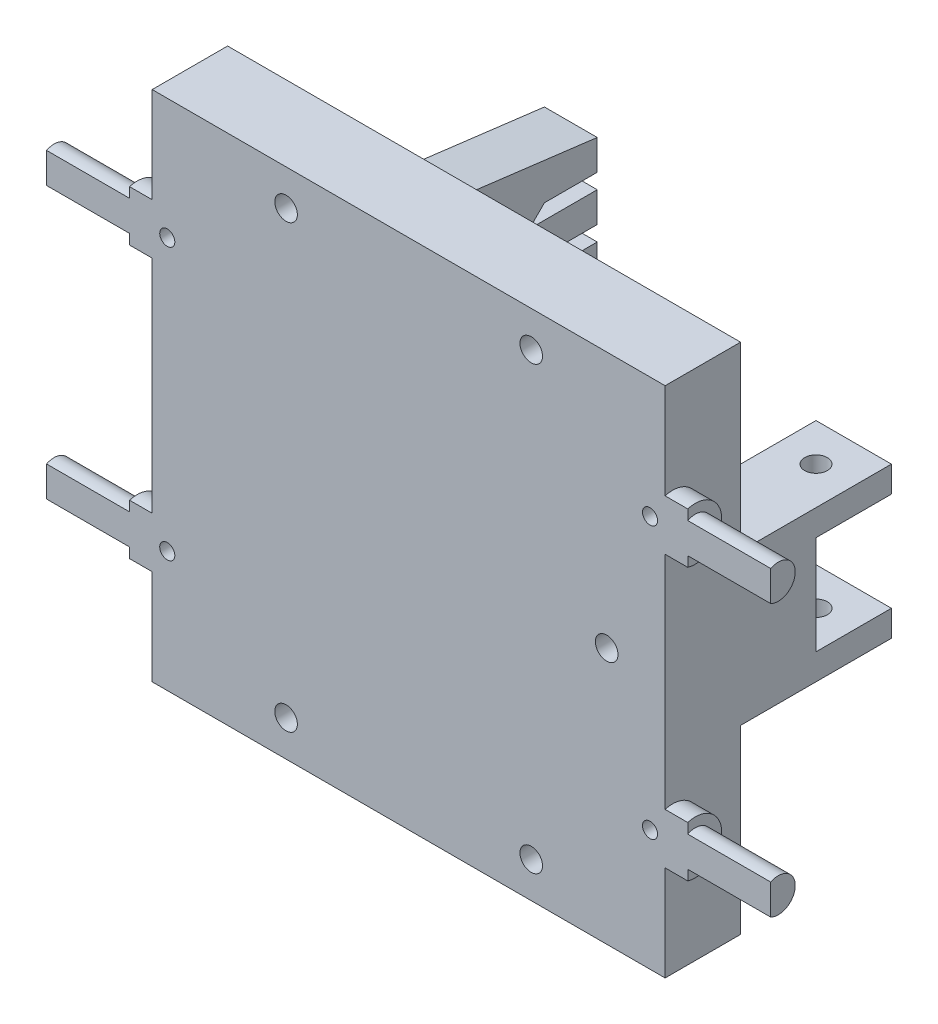
SolidWorks part; units mm, degrees
ref_plane "Front Plane" through (0, 0, 0) normal (0, 0, 1) x (1, 0, 0)
ref_plane "Top Plane" through (0, 0, 0) normal (0, 1, 0) x (1, 0, 0)
ref_plane "Right Plane" through (0, 0, 0) normal (1, 0, 0) x (0, 0, -1)
sketch "Sketch1" plane through (0, 0, 0) normal (0, 0, 1) x (1, 0, 0)
  line L1 (0, 0) -> (-68, 0)
  line L2 (0, 0) -> (0, -68)
  line L3 (0, -68) -> (-68, -68)
  line L4 (-68, 0) -> (-68, -68)
  dimension "D1" = 68
  dimension "D2" = 68
extrude "Boss-Extrude1" add sketch "Sketch1" along normal blind 10
sketch "Sketch2" plane through (-68, 0, 0) normal (-1, 0, 0) x (0, 0, 1)
  line L1 (10, 0) -> (0, 0) construction
  line L2 (10, -68) -> (0, -68) construction
  line L3 (10, 0) -> (10, -68) construction
  line L4 (10, 0) -> (10, -68)
  circle A0 centre (9, -52) radius 3.5
  circle A1 centre (9, -16) radius 3.5
  dimension "D1" = 7
  dimension "D2" = 7
  dimension "D3" = 1
  dimension "D4" = 0
  dimension "D5" = 16
  dimension "D6" = 16
extrude "Boss-Extrude2" add sketch "Sketch2" along normal blind 3 contours L4 A1 | L4 A0
sketch "Sketch3" plane through (-71, 0, 0) normal (-1, 0, 0) x (0, 0, 1)
  line L0 (10, -55.3541) -> (10, -12.6459)
  circle A0 centre (9, -52) radius 2.25
  circle A1 centre (9, -16) radius 2.25
  dimension "D1" = 4.5
  dimension "D2" = 4.5
extrude "Boss-Extrude3" add sketch "Sketch3" along normal blind 11 contours L0 A0 | L0 A1
sketch "Sketch4" plane through (0, 0, 0) normal (1, 0, 0) x (0, 0, -1)
  line L0 (-10, 0) -> (0, 0) construction
  line L1 (-10, -68) -> (0, -68) construction
  line L2 (-10, 0) -> (-10, -68)
  circle A0 centre (-9, -16) radius 3.5
  circle A1 centre (-9, -52) radius 3.5
  dimension "D1" = 16
  dimension "D2" = 16
  dimension "D3" = 7
  dimension "D4" = 7
  dimension "D5" = 1
  dimension "D6" = 0
extrude "Boss-Extrude4" add sketch "Sketch4" along normal blind 3 contours L2 A0 | L2 A1
sketch "Sketch5" plane through (3, 0, 0) normal (1, 0, 0) x (0, 0, -1)
  line L0 (-10, -12.6459) -> (-10, -55.3541)
  circle A0 centre (-9, -16) radius 2.25
  circle A1 centre (-9, -52) radius 2.25
  dimension "D1" = 4.5
  dimension "D2" = 4.5
extrude "Boss-Extrude5" add sketch "Sketch5" along normal blind 11 contours L0 A0 | L0 A1
sketch "Sketch6" plane through (0, 0, 0) normal (0, 0, -1) x (-1, 0, 0)
  line L0 (0, -34) -> (68, -34) construction
  line L1 (55.25, -12.75) -> (12.75, -12.75)
  line L2 (55.25, -12.75) -> (55.25, -55.25)
  line L3 (55.25, -55.25) -> (12.75, -55.25)
  line L4 (12.75, -12.75) -> (12.75, -55.25)
  line L5 (0, -68) -> (0, 0) construction
  line L6 (68, 0) -> (68, -68) construction
  line L7 (34, 0) -> (34, -68) construction
  line L8 (0, 0) -> (68, 0) construction
  line L9 (68, -68) -> (0, -68) construction
  point P16 (12.75, -34)
  point P17 (34, -55.25)
  dimension "D1" = 42.5
  dimension "D2" = 42.5
  dimension "D3" = 0
  dimension "D4" = 0
extrude "Cut-Extrude1" cut sketch "Sketch6" against normal blind 3
sketch "Sketch8" plane through (0, 0, 0) normal (0, 0, -1) x (-1, 0, 0)
  line L0 (55.25, -12.75) -> (12.75, -12.75) construction
  line L2 (12.75, -12.75) -> (12.75, -55.25) construction
  line L3 (34, 0) -> (34, -108.8236) construction
  line L4 (0, 0) -> (68, 0) construction
  line L5 (0, -34) -> (112.3527, -34) construction
  line L6 (0, -68) -> (0, 0) construction
  circle A0 centre (17.75, -4.75) radius 1.5
  circle A3 centre (50.25, -4.75) radius 1.5
  circle A4 centre (50.25, -63.25) radius 1.5
  circle A5 centre (17.75, -63.25) radius 1.5
  dimension "D1" = 8
  dimension "D3" = 3
  dimension "D5" = 5
extrude "Cut-Extrude2" cut sketch "Sketch8" against normal blind 15
sketch "Sketch9" plane through (0, 0, 0) normal (0, 0, -1) x (-1, 0, 0)
  line L1 (0, -24) -> (10, -24)
  line L2 (0, -24) -> (0, -44)
  line L3 (0, -44) -> (10, -44)
  line L4 (10, -24) -> (10, -44)
  line L6 (0, -68) -> (0, 0) construction
  point P4 (0, -34)
  point P7 (0, -34)
  dimension "D1" = 0
  dimension "D2" = 20
  dimension "D3" = 0
  dimension "D4" = 10
  dimension "D5" = 90
  dimension "D6" = 90
  dimension "D7" = 90
extrude "Boss-Extrude6" add sketch "Sketch9" along normal blind 20
sketch "Sketch10" plane through (0, 0, 0) normal (0, 0, -1) x (-1, 0, 0)
  line L0 (0, -56) -> (23.3312, -56) construction
  line L1 (0, -68) -> (0, -44) construction
  line L2 (12.75, -12.75) -> (12.75, -55.25) construction
  line L3 (10, -44) -> (10, -24) construction
  circle A0 centre (7.75, -34) radius 1.5
  circle A1 centre (7.75, -78) radius 1.5
  point P10 (10, -34)
  dimension "D1" = 3
  dimension "D2" = 5
  dimension "D3" = 0
extrude "Cut-Extrude3" cut sketch "Sketch10" against normal blind 10
sketch "Sketch11" plane through (0, 0, 10) normal (0, 0, 1) x (1, 0, 0)
  line L0 (-68, -34) -> (19.7059, -34) construction
  line L1 (-68, -19.3541) -> (-68, -48.6459) construction
  line L2 (-34, -68) -> (-34, 32.0149) construction
  line L3 (-68, -68) -> (0, -68) construction
  line L4 (-82, -54.0156) -> (-82, -49.9844) construction
  circle A0 centre (-66, -52) radius 1
  circle A1 centre (-66, -16) radius 1
  circle A2 centre (-2, -52) radius 1
  circle A3 centre (-2, -16) radius 1
  point P12 (-82, -52)
  dimension "D1" = 16
  dimension "D2" = 0
  dimension "D3" = 2
extrude "Cut-Extrude4" cut sketch "Sketch11" against normal blind 20
sketch "Sketch13" plane through (0, 0, 0) normal (0, 0, -1) x (-1, 0, 0)
  line L0 (68, 0) -> (68, -68) construction
  line L1 (59, -26) -> (66, -26)
  line L2 (59, -26) -> (59, -42)
  line L3 (59, -42) -> (66, -42)
  line L4 (66, -26) -> (66, -42)
  point P4 (66, -34)
  point P7 (68, -34)
  dimension "D1" = 7
  dimension "D2" = 0
  dimension "D3" = 16
  dimension "D4" = 2
extrude "Boss-Extrude7" add sketch "Sketch13" along normal blind 40
sketch "Sketch15" plane through (-66, 0, 0) normal (-1, 0, 0) x (0, 0, 1)
  line L0 (-40, -34) -> (24.0661, -34) construction
  line L1 (-40, -42) -> (-40, -26) construction
  line L2 (-40, -32) -> (-31, -32)
  line L3 (-31, -32) -> (-33, -30)
  line L4 (-33, -30) -> (-40, -30)
  line L5 (-40, -30) -> (-40, -32)
  line L6 (-40, -26) -> (0, -26) construction
  line L7 (-40, -38) -> (-40, -36)
  line L8 (-31, -36) -> (-33, -38)
  line L9 (-33, -38) -> (-40, -38)
  line L10 (-40, -36) -> (-31, -36)
  dimension "D1" = 2
  dimension "D2" = 4
  dimension "D3" = 45
  dimension "D4" = 7
extrude "Cut-Extrude5" cut sketch "Sketch15" against normal blind 10
sketch "Sketch16" plane through (-66, 0, 0) normal (-1, 0, 0) x (0, 0, 1)
  line L0 (0, -26) -> (-40, -26)
  line L1 (-40, -26) -> (0, -21)
  line L2 (0, -21) -> (0, -26)
  line L3 (-40, -34) -> (21.219, -34) construction
  line L4 (-40, -36) -> (-40, -32) construction
  line L5 (-40, -42) -> (0, -47)
  line L6 (0, -42) -> (-40, -42)
  line L7 (0, -47) -> (0, -42)
  dimension "D1" = 5
extrude "Boss-Extrude8" add sketch "Sketch16" against normal up to vertex
sketch "Sketch17" plane through (0, 0, -20) normal (0, 0, -1) x (-1, 0, 0)
  line L1 (0, -27.45) -> (10, -27.45)
  line L2 (0, -27.45) -> (0, -40.55)
  line L3 (0, -40.55) -> (10, -40.55)
  line L4 (10, -27.45) -> (10, -40.55)
  line L5 (10, -44) -> (10, -24) construction
  line L6 (0, -24) -> (0, -44) construction
  point P4 (0, -34)
  point P9 (0, -34)
  dimension "D1" = 0
  dimension "D2" = 13.1
  dimension "D3" = 0
extrude "Cut-Extrude6" cut sketch "Sketch17" against normal blind 10
sketch "Sketch18" plane through (0, -44, 0) normal (0, -1, 0) x (-1, 0, 0)
  line L0 (0, 20) -> (10, 20) construction
  line L1 (0, 10) -> (0, 20) construction
  circle A0 centre (5, 15) radius 1.5
  point P4 (5, 20)
  point P7 (0, 15)
  dimension "D1" = 0
  dimension "D2" = 0
  dimension "D3" = 3
extrude "Cut-Extrude7" cut sketch "Sketch18" against normal blind 30
